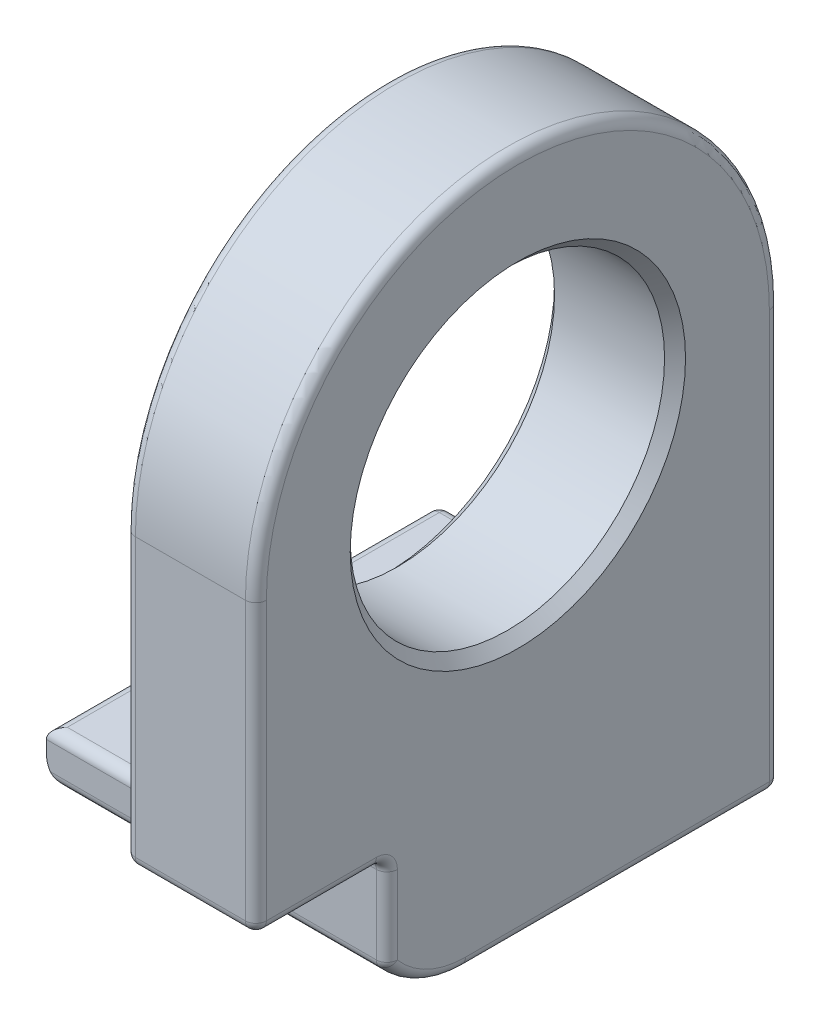
SolidWorks part; units mm, degrees
ref_plane "前视基准面" through (0, 0, 0) normal (0, 0, 1) x (1, 0, 0)
ref_plane "上视基准面" through (0, 0, 0) normal (0, 1, 0) x (1, 0, 0)
ref_plane "右视基准面" through (0, 0, 0) normal (1, 0, 0) x (0, 0, -1)
sketch "草图1" plane through (0, 0, 0) normal (1, 0, 0) x (0, 0, -1)
  line L0 (-5, 0) -> (-5, -8)
  line L1 (5, 0) -> (5, -8)
  line L2 (5, -8) -> (-5, -8)
  circle A0 centre (0, 0) radius 3
  arc A1 (5, 0) -> (-5, 0) centre (0, 0) ccw
extrude "凸台-拉伸1" add sketch "草图1" along normal blind 2.5
sketch "草图2" plane through (0, -8, 0) normal (0, -1, 0) x (1, 0, 0)
  line L1 (2.5, -5) -> (-4, -5)
  line L3 (2.5, 5) -> (-4, 5)
  line L4 (-4, -5) -> (-4, 5)
  line L6 (0, 5) -> (0, -5) construction
  line L8 (2.5, -5) -> (2.5, 5)
  circle A0 centre (-2, 0.5) radius 0.8
  circle A1 centre (-2, -3) radius 0.8
  dimension "D1" = 4
  dimension "D3" = 1.6
  dimension "D7" = 2
  dimension "D2" = 2
  dimension "D4" = 5.5
extrude "凸台-拉伸2" add sketch "草图2" against normal blind 1.5
sketch "草图3" plane through (2.5, 0, 0) normal (1, 0, 0) x (0, 0, -1)
  circle A0 centre (0, 0) radius 3.9779
sketch "草图5" plane through (0, -8, 0) normal (0, -1, 0) x (1, 0, 0)
  line L1 (2.5, 5) -> (2.5, -5) construction
  line L3 (-4, 5) -> (2.5, 5)
  line L4 (-4, 5) -> (-4, 2.5)
  line L5 (-4, 2.5) -> (2.5, 2.5)
  line L6 (2.5, 5) -> (2.5, 2.5)
extrude "切除-拉伸1" cut sketch "草图5" against normal blind 2.5
sketch "草图6" plane through (-4, 0, 0) normal (-1, 0, 0) x (0, 0, 1)
  line L2 (2.8974, -6) -> (3.2771, -6)
  line L3 (1, -8) -> (1, -8.3251)
  line L4 (1, -8.3251) -> (3.2771, -8.3251)
  line L5 (3.2771, -6) -> (3.2771, -8.3251)
  arc A0 (1, -8) -> (2.8974, -6) centre (1, -6.1) ccw
extrude "切除-拉伸2" cut sketch "草图6" against normal up to next
fillet "圆角1" radius 0.2 1 edges at (0, -6.5, -1.25)
fillet "圆角2" radius 0.2 24 edges at (-2.1, -6.5, -5) (2.5, -4, -5) (2.5, -2.75, 5) (-0.0586, -6.4414, -5) (0, -3.15, -5) (0, -2.75, 5) (-4, -6.5, -1.25) (-4, -8, -2) (-4, -7.25, -5) (2.5, 5, 0) (0, 5, 0) (2.5, -5.5, 3.75) (0, -5.5, 3.75) (1.25, -5.5, 5) (-4, -7.8067, 1.8349) (-0.75, -8, -5) (2.5, -6.3831, 2.5) (2.5, -8, -2) (0, -5.9, 2.5) (-0.0586, -6.4414, 2.5) (2.5, -7.8067, 1.8349) (-0.75, -7.2662, 2.5) (1.25, -5.5, 2.5) (-2.1, -6.5, 2.5)
chamfer "倒角1" distance 0.2 angle 45 2 edges at (0, 0, -3) (2.5, 0, -3)
